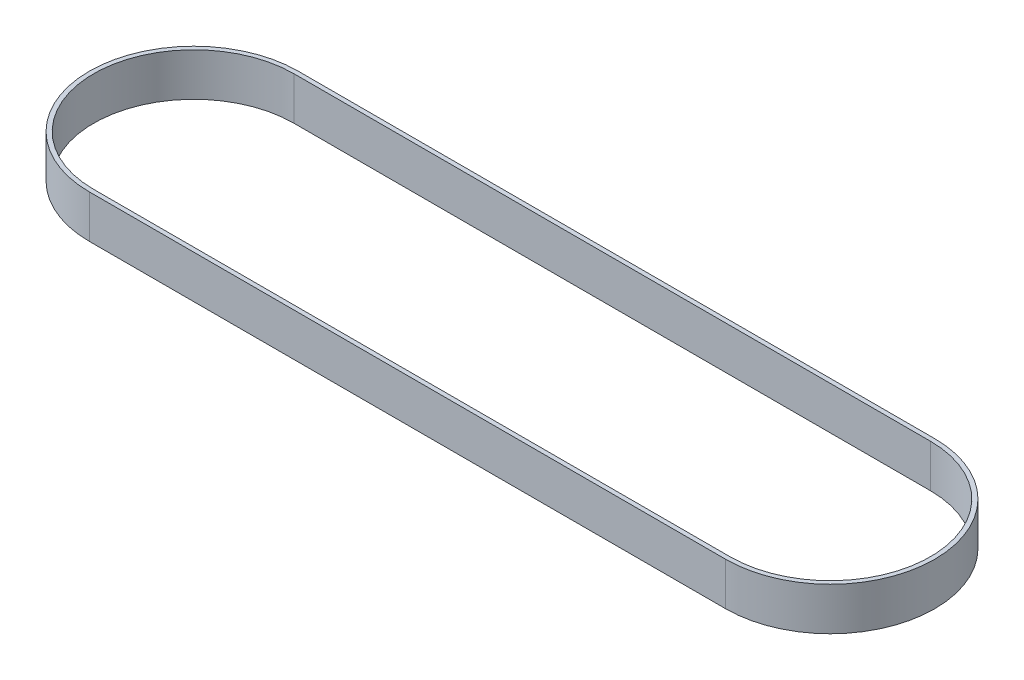
SolidWorks part; units mm, degrees
ref_plane "Front Plane" through (0, 0, 0) normal (0, 0, 1) x (1, 0, 0)
ref_plane "Top Plane" through (0, 0, 0) normal (0, 1, 0) x (1, 0, 0)
ref_plane "Right Plane" through (0, 0, 0) normal (1, 0, 0) x (0, 0, -1)
sketch "Sketch1" plane through (0, 0, 0) normal (0, 1, 0) x (1, 0, 0)
  line L0 (0, 0) -> (222.5548, 0) construction
  line L1 (0, 35.0139) -> (222.5548, 35.0139)
  line L2 (0, -35.0139) -> (222.5548, -35.0139)
  line L3 (0, -36.5379) -> (222.5548, -36.5379)
  line L4 (0, 36.5379) -> (222.5548, 36.5379)
  arc A0 (0, 35.0139) -> (0, -35.0139) centre (0, 0) ccw
  arc A1 (222.5548, -35.0139) -> (222.5548, 35.0139) centre (222.5548, 0) ccw
  arc A2 (0, 36.5379) -> (0, -36.5379) centre (0, 0) ccw
  arc A3 (222.5548, -36.5379) -> (222.5548, 36.5379) centre (222.5548, 0) ccw
  dimension "D2" = 70.0278
  dimension "D3" = 222.5548
  dimension "D4" = 1.524
extrude "Boss-Extrude1" add sketch "Sketch1" along normal blind 15
